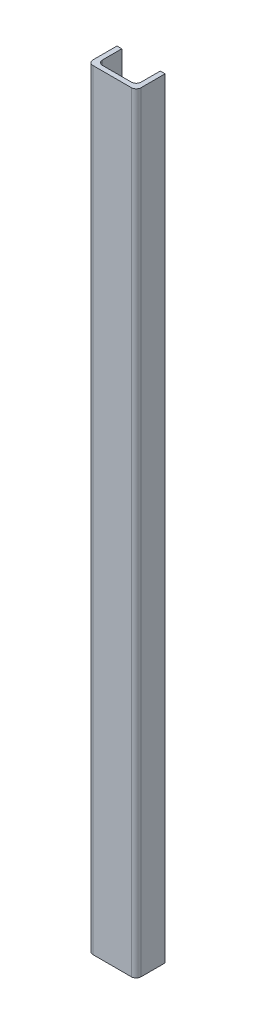
SolidWorks part; units mm, degrees
ref_plane "Front Plane" through (0, 0, 0) normal (0, 0, 1) x (1, 0, 0)
ref_plane "Top Plane" through (0, 0, 0) normal (0, 1, 0) x (1, 0, 0)
ref_plane "Right Plane" through (0, 0, 0) normal (1, 0, 0) x (0, 0, -1)
sketch "Sketch1" plane through (0, 0, 0) normal (0, 1, 0) x (1, 0, 0)
  line L5 (-15, 2.5) -> (15, 2.5)
  line L7 (-20, -2.5) -> (20, -2.5)
  line L9 (-25, 27.5) -> (-20, 27.5)
  line L10 (-25, 27.5) -> (-25, 2.5)
  line L12 (-20, 27.5) -> (-20, 7.5)
  line L14 (25, 2.5) -> (25, 27.5)
  line L15 (25, 27.5) -> (20, 27.5)
  line L16 (20, 7.5) -> (20, 27.5)
  arc A0 (15, 2.5) -> (20, 7.5) centre (15, 7.5) ccw
  arc A1 (-15, 2.5) -> (-20, 7.5) centre (-15, 7.5) cw
  arc A2 (20, -2.5) -> (25, 2.5) centre (20, 2.5) ccw
  arc A3 (-25, 2.5) -> (-20, -2.5) centre (-20, 2.5) ccw
  point P18 (25, -2.5)
  point P21 (-25, -2.5)
  dimension "D9" = 5
  dimension "D8" = 5
  dimension "D1" = 50
  dimension "D2" = 30
  dimension "D3" = 25
  dimension "D4" = 2.5
  dimension "D5" = 5
  dimension "D6" = 30
  dimension "D7" = 5
extrude "Boss-Extrude2" add sketch "Sketch1" along normal blind 800
